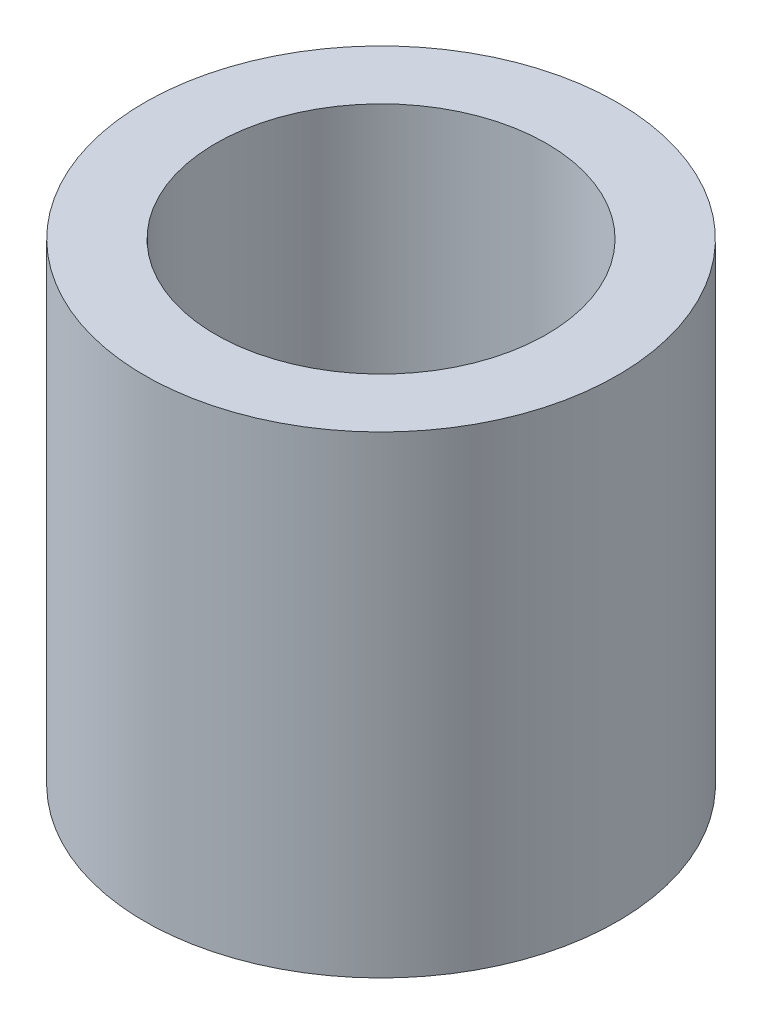
SolidWorks part; units mm, degrees
ref_plane "Front Plane" through (0, 0, 0) normal (0, 0, 1) x (1, 0, 0)
ref_plane "Top Plane" through (0, 0, 0) normal (0, 1, 0) x (1, 0, 0)
ref_plane "Right Plane" through (0, 0, 0) normal (1, 0, 0) x (0, 0, -1)
sketch "Sketch1" plane through (0, 0, 0) normal (0, 0, 1) x (1, 0, 0)
  line L0 (0, 0) -> (0, 5.2661) construction
  line L2 (-1.75, 0) -> (-2.5, 0)
  line L3 (-1.75, 0) -> (-1.75, 5)
  line L4 (-1.75, 5) -> (-2.5, 5)
  line L5 (-2.5, 0) -> (-2.5, 5)
  dimension "D1" = 5
  dimension "D2" = 3.5
  dimension "D3" = 5
revolve "Revolve1" add sketch "Sketch1" angle 360 about L0
